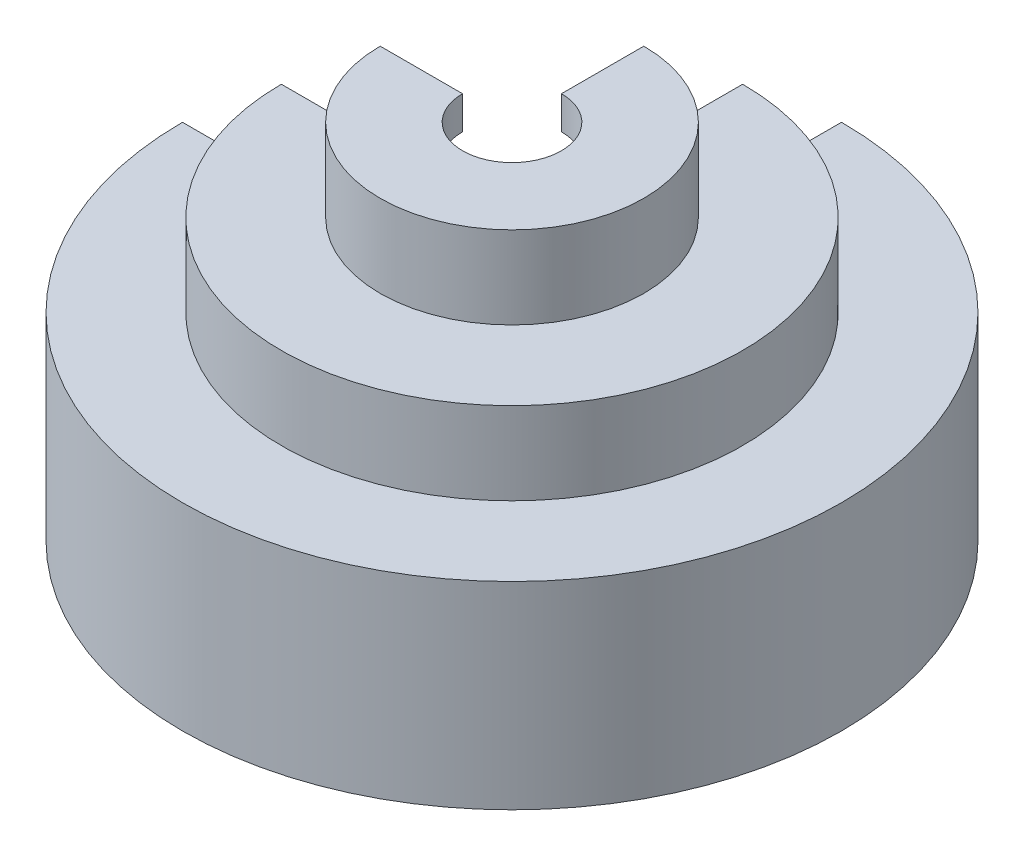
SolidWorks part; units mm, degrees
ref_plane "Front Plane" through (0, 0, 0) normal (0, 0, 1) x (1, 0, 0)
ref_plane "Top Plane" through (0, 0, 0) normal (0, 1, 0) x (1, 0, 0)
ref_plane "Right Plane" through (0, 0, 0) normal (1, 0, 0) x (0, 0, -1)
sketch "Sketch1" plane through (0, 0, 0) normal (0, 0, 1) x (1, 0, 0)
  line L0 (0, -150) -> (0, 150) construction
  line L1 (-30, 150) -> (-80, 150)
  line L2 (-80, 150) -> (-80, 100)
  line L3 (-80, 100) -> (-140, 100)
  line L4 (-140, 100) -> (-140, 50)
  line L5 (-140, 50) -> (-200, 50)
  line L6 (-200, 50) -> (-200, -70)
  line L7 (-200, -70) -> (-80, -70)
  line L8 (-80, -70) -> (-80, -150)
  line L9 (-80, -150) -> (-40, -150)
  line L10 (-40, -150) -> (-40, -30)
  line L11 (-40, -30) -> (-140, -30)
  line L12 (-140, -30) -> (-140, 30)
  line L13 (-140, 30) -> (-80, 30)
  line L14 (-80, 30) -> (-80, 80)
  line L17 (-80, 80) -> (-50, 80)
  line L18 (-50, 80) -> (-50, 130)
  line L19 (-50, 130) -> (-30, 130)
  line L20 (-30, 130) -> (-30, 150)
  dimension "D1" = 300
  dimension "D2" = 40
  dimension "D3" = 30
  dimension "D4" = 120
  dimension "D5" = 300
  dimension "D6" = 60
  dimension "D7" = 100
  dimension "D8" = 20
  dimension "D9" = 20
  dimension "D10" = 30
  dimension "D11" = 50
  dimension "D12" = 50
  dimension "D13" = 50
  dimension "D14" = 50
  dimension "D15" = 40
  dimension "D16" = 60
  dimension "D17" = 60
  dimension "D18" = 120
revolve "Revolve1" add sketch "Sketch1" angle 360 about L0
sketch "Sketch2" plane through (0, 150, 0) normal (0, 1, 0) x (1, 0, 0)
  line L0 (0, 0) -> (-278.0365, 0)
  line L1 (-278.0365, 0) -> (-278.0365, 207.4662)
  line L2 (-278.0365, 207.4662) -> (0, 207.4662)
  line L3 (0, 207.4662) -> (0, 0)
  dimension "D1" = 207.4662
  dimension "D2" = 278.0365
extrude "Cut-Extrude1" cut sketch "Sketch2" against normal through all
